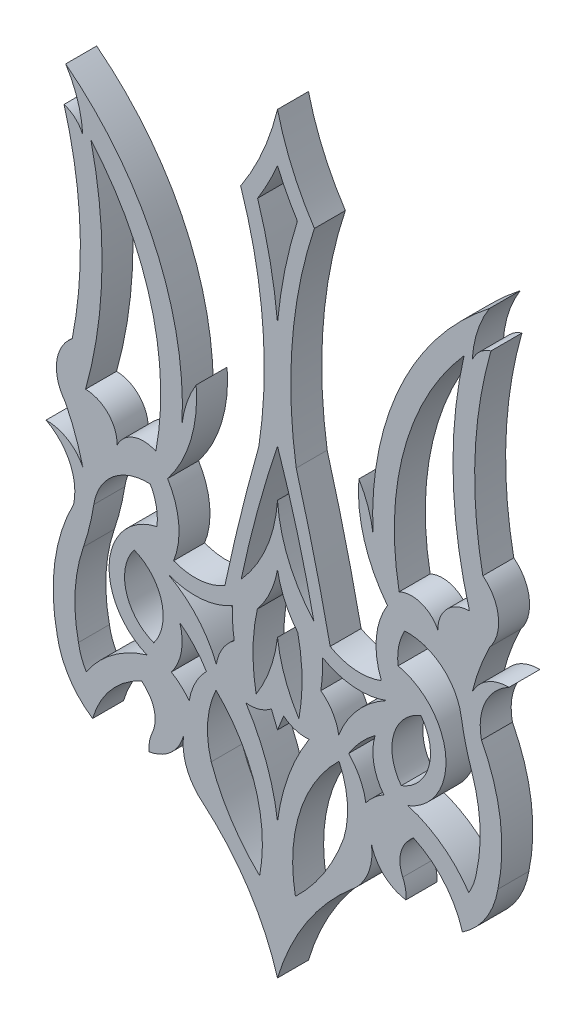
SolidWorks part; units mm, degrees
ref_plane "Спереди" through (0, 0, 0) normal (0, 0, 1) x (1, 0, 0)
ref_plane "Сверху" through (0, 0, 0) normal (0, 1, 0) x (1, 0, 0)
ref_plane "Справа" through (0, 0, 0) normal (1, 0, 0) x (0, 0, -1)
sketch "Эскиз1" [suppressed] plane through (0, 0, 0) normal (0, 0, 1) x (1, 0, 0)
  line L0 (87.6443, -23.7883) -> (87.6443, -6.8916) construction
  line L1 (87.6443, -6.8916) -> (87.6443, 352.3548) construction
  line L3 (87.6443, 68.6318) -> (85.6546, 73.5186)
  line L4 (87.6443, 68.6318) -> (89.6341, 73.5186)
  arc A0 (40.6207, 123.507) -> (44.6469, 97.5316) centre (120.5444, 122.5954) ccw
  arc A1 (40.6207, 123.507) -> (52.5559, 106.1421) centre (-51.0479, 47.7173) cw
  arc A2 (44.6469, 97.5316) -> (48.9353, 94.2011) centre (41.1464, 88.5981) cw
  arc A3 (48.9353, 94.2011) -> (48.9353, 107.9589) centre (131.9116, 101.08) cw
  arc A4 (52.5559, 106.1421) -> (53.1645, 101.095) centre (43.5258, 102.4931) cw
  arc A6 (53.1645, 101.095) -> (49.4634, 108.1691) centre (60.7326, 109.5597) cw
  arc A7 (48.935, 107.9555) -> (49.4634, 108.1691) centre (50.0675, 105.914) cw
  arc A8 (64.6822, 73.5186) -> (59.1188, 62.4923) centre (79.1678, 59.2931) ccw
  arc A9 (59.1188, 62.4923) -> (53.3348, 67.6488) centre (43.2754, 50.5432) ccw
  arc A10 (53.3348, 67.6488) -> (56.4809, 74.2644) centre (31.6379, 82.0231) ccw
  arc A11 (56.4809, 74.2644) -> (56.1084, 82.846) centre (34.8221, 77.623) ccw
  arc A12 (64.6822, 73.5186) -> (56.1084, 82.846) centre (35.8416, 55.6125) ccw
  arc A13 (41.6181, 95.7087) -> (47.5094, 72.7815) centre (35.854, 82.0071) cw
  arc A14 (41.6181, 95.7087) -> (47.5094, 72.7815) centre (53.0477, 86.4251) ccw
  arc A15 (25.6081, 56.3356) -> (38.7862, 66.0056) centre (60.8247, 22.1574) cw
  arc A16 (38.7862, 66.0056) -> (32.0434, 81.1637) centre (52.0503, 80.9846) cw
  arc A17 (40.0148, 95.7087) -> (32.0434, 81.1637) centre (52.4098, 79.4588) ccw
  arc A18 (40.0148, 95.7087) -> (34.589, 93.5264) centre (39.084, 90.1868) ccw
  arc A19 (41.6181, 98.1673) -> (34.1719, 94.2011) centre (40.4092, 91.464) ccw
  arc A20 (30.5806, 109.6374) -> (41.6181, 98.1673) centre (116.5629, 181.3309) ccw
  arc A21 (30.5806, 109.6374) -> (31.6379, 83.1978) centre (-35.2023, 93.7659) cw
  arc A22 (25.6081, 56.3356) -> (31.6379, 83.1978) centre (108.2418, 51.8945) cw
  arc A23 (34.1719, 94.2011) -> (34.589, 93.5264) centre (34.7179, 94.0723) ccw
  arc A24 (72.6436, 90.9214) -> (73.3927, 85.212) centre (115.3568, 93.6216) ccw
  arc A25 (70.0758, 80.9846) -> (73.3927, 85.212) centre (104.2196, 57.6099) cw
  arc A26 (70.0758, 80.9846) -> (60.9509, 89.3983) centre (44.0092, 61.8694) ccw
  arc A27 (60.9509, 89.3983) -> (72.6436, 90.9214) centre (64.518, 107.658) ccw
  arc A28 (80.7379, 32.2385) -> (67.7808, 69.8254) centre (31.257, 36.2081) ccw
  arc A29 (64.9288, 57.4953) -> (67.7808, 69.8254) centre (93.0087, 57.4953) cw
  arc A30 (80.7379, 32.2385) -> (64.9288, 57.4953) centre (119.8675, 74.307) cw
  arc A31 (94.5508, 32.2385) -> (110.3598, 57.4953) centre (55.4212, 74.307) ccw
  arc A32 (110.3598, 57.4953) -> (107.5079, 69.8254) centre (82.28, 57.4953) ccw
  arc A33 (94.5508, 32.2385) -> (107.5079, 69.8254) centre (144.0316, 36.2081) cw
  arc A34 (114.3378, 89.3983) -> (102.6451, 90.9214) centre (110.7707, 107.658) cw
  arc A35 (105.2129, 80.9846) -> (114.3378, 89.3983) centre (131.2795, 61.8694) cw
  arc A36 (105.2129, 80.9846) -> (101.896, 85.212) centre (71.069, 57.6099) ccw
  arc A37 (102.6451, 90.9214) -> (101.896, 85.212) centre (59.9318, 93.6216) cw
  arc A38 (141.1167, 94.2011) -> (140.6996, 93.5264) centre (140.5708, 94.0723) cw
  arc A39 (149.6806, 56.3356) -> (143.6508, 83.1978) centre (67.0469, 51.8945) ccw
  arc A40 (144.708, 109.6374) -> (143.6508, 83.1978) centre (210.491, 93.7659) ccw
  arc A41 (144.708, 109.6374) -> (133.6706, 98.1673) centre (58.7258, 181.3309) cw
  arc A42 (133.6706, 98.1673) -> (141.1167, 94.2011) centre (134.8795, 91.464) cw
  arc A43 (135.2739, 95.7087) -> (140.6996, 93.5264) centre (136.2047, 90.1868) cw
  arc A44 (135.2739, 95.7087) -> (143.2453, 81.1637) centre (122.8789, 79.4588) cw
  arc A45 (136.5025, 66.0056) -> (143.2453, 81.1637) centre (123.2384, 80.9846) ccw
  arc A46 (149.6806, 56.3356) -> (136.5025, 66.0056) centre (114.4639, 22.1574) ccw
  arc A47 (133.6706, 95.7087) -> (127.7793, 72.7815) centre (122.241, 86.4251) cw
  arc A48 (133.6706, 95.7087) -> (127.7793, 72.7815) centre (139.4347, 82.0071) ccw
  arc A49 (110.6065, 73.5186) -> (119.1803, 82.846) centre (139.4471, 55.6125) cw
  arc A50 (118.8077, 74.2644) -> (119.1803, 82.846) centre (140.4665, 77.623) cw
  arc A51 (121.9539, 67.6488) -> (118.8077, 74.2644) centre (143.6508, 82.0231) cw
  arc A52 (116.1699, 62.4923) -> (121.9539, 67.6488) centre (132.0132, 50.5432) cw
  arc A53 (110.6065, 73.5186) -> (116.1699, 62.4923) centre (96.1209, 59.2931) cw
  arc A54 (126.3537, 107.9555) -> (125.8253, 108.1691) centre (125.2211, 105.914) ccw
  arc A55 (122.1242, 101.095) -> (125.8253, 108.1691) centre (114.5561, 109.5597) ccw
  arc A56 (122.7327, 106.1421) -> (122.1242, 101.095) centre (131.7628, 102.4931) ccw
  arc A57 (126.3534, 94.2011) -> (126.3534, 107.9589) centre (43.3771, 101.08) ccw
  arc A58 (130.6418, 97.5316) -> (126.3534, 94.2011) centre (134.1423, 88.5981) ccw
  arc A59 (134.668, 123.507) -> (122.7327, 106.1421) centre (226.3366, 47.7173) ccw
  arc A60 (134.668, 123.507) -> (130.6418, 97.5316) centre (54.7443, 122.5954) cw
  arc A61 (75.9102, 104.8888) -> (87.6443, 132.8603) centre (41.1732, 135.9081) ccw
  arc A62 (75.9102, 104.8888) -> (87.6443, 148.0034) centre (451.7712, 25.7481) cw
  arc A63 (99.3785, 104.8888) -> (87.6443, 132.8603) centre (134.1154, 135.9081) cw
  arc A64 (99.3785, 104.8888) -> (87.6443, 148.0034) centre (-276.4825, 25.7481) ccw
  arc A65 (85.6546, 73.5186) -> (81.8714, 71.5335) centre (82.7705, 74.4176) cw
  arc A66 (87.6443, 53.083) -> (81.8714, 71.5335) centre (17.8027, 41.3588) ccw
  arc A67 (89.6341, 73.5186) -> (93.4173, 71.5335) centre (92.5182, 74.4176) ccw
  arc A68 (87.6443, 53.083) -> (93.4173, 71.5335) centre (157.486, 41.3588) cw
  arc A69 (87.6443, 111.5019) -> (75.9102, 93.6216) centre (57.0652, 118.7792) cw
  arc A70 (75.9102, 93.6216) -> (76.8685, 89.0118) centre (107.3806, 97.7594) ccw
  arc A71 (76.8685, 89.0118) -> (83.3447, 99.1087) centre (-45.6127, 174.6974) ccw
  arc A72 (83.3447, 99.1087) -> (78.1463, 84.8771) centre (62.4821, 98.6641) cw
  arc A73 (80.7379, 75.1856) -> (78.1463, 84.8771) centre (94.8769, 84.1588) cw
  arc A74 (80.7379, 75.1856) -> (83.7649, 75.1856) centre (82.2514, 76.6992) ccw
  arc A75 (83.7649, 75.1856) -> (82.2514, 83.8045) centre (69.0111, 77.037) ccw
  arc A76 (87.6443, 99.1626) -> (82.2514, 83.8045) centre (61.1079, 99.8548) cw
  arc A77 (91.5237, 75.1856) -> (93.0373, 83.8045) centre (106.2776, 77.037) cw
  arc A78 (94.5508, 75.1856) -> (91.5237, 75.1856) centre (93.0373, 76.6992) cw
  arc A79 (94.5508, 75.1856) -> (97.1424, 84.8771) centre (80.4118, 84.1588) ccw
  arc A80 (91.944, 99.1087) -> (97.1424, 84.8771) centre (112.8066, 98.6641) ccw
  arc A81 (98.4202, 89.0118) -> (91.944, 99.1087) centre (220.9014, 174.6974) cw
  arc A82 (99.3785, 93.6216) -> (98.4202, 89.0118) centre (67.908, 97.7594) cw
  arc A83 (87.6443, 111.5019) -> (99.3785, 93.6216) centre (118.2235, 118.7792) ccw
  arc A84 (87.6443, 99.1626) -> (93.0373, 83.8045) centre (114.1808, 99.8548) ccw
  spline S0 degree 3 poles (82.1027, 12.4657) (79.9341, 18.6914) (72.2067, 24.3569) (65.9185, 33.1059) (62.5505, 37.466) (60.1799, 39.943) (59.1555, 43.0897) (57.2647, 45.5543) (57.6286, 48.5225) (57.2368, 50.5201) (57.9183, 52.5735) (56.9495, 53.1909) (55.4861, 53.2614) (56.2486, 51.0634) (55.1896, 49.5498) (54.5036, 47.9051) (53.4075, 46.7279) (51.1035, 46.9894) (53.4402, 48.5489) (52.9045, 50.4248) (53.1315, 52.5819) (50.2686, 54.9996) (47.2077, 56.7477) (43.7411, 62.1873) (40.1307, 57.0478) (36.3563, 55.4003) (34.0123, 52.1175) (31.6232, 49.6208) (29.9193, 47.1505) (28.3136, 45.324) (28.3685, 43.599) (28.0916, 41.1132) (25.4838, 45.8805) (23.6707, 48.1541) (21.3506, 53.1893) (17.5941, 56.1294) (15.6148, 61.936) (15.5097, 68.0525) (15.9741, 74.6221) (17.289, 80.1758) (19.034, 85.376) (20.3139, 90.1381) (21.7721, 94.5747) (21.6409, 98.6721) (22.3333, 102.2806) (22.4635, 106.0403) (21.2552, 109.3896) (20.4336, 112.3281) (19.1765, 114.309) (17.3368, 115.252) (16.6151, 116.5408) (13.9501, 117.1637) (16.6597, 117.6233) (18.0151, 116.3143) (20.2861, 115.5733) (22.0029, 113.6892) (23.906, 112.8857) (24.7011, 110.1686) (25.9462, 111.2271) (24.8035, 113.2315) (24.159, 115.7716) (22.1122, 118.6068) (20.8946, 121.9867) (19.3322, 125.5441) (17.6129, 129.5089) (17.4458, 134.0046) (17.2957, 140.0912) (22.0505, 144.124) (21.6416, 148.9774) (21.7935, 153.6259) (21.4811, 159.1076) (22.6432, 165.8126) (23.1995, 173.1345) (24.6232, 181.9748) (23.765, 191.5281) (23.3918, 198.8905) (20.9362, 204.2846) (19.4503, 205.9635) (18.8575, 209.3893) (19.9586, 207.7428) (21.3919, 207.2624) (22.9247, 206.0347) (23.8774, 204.8209) (24.7322, 203.1653) (25.4143, 204.4362) (24.9731, 205.9617) (24.8711, 208.3515) (23.8043, 211.5847) (22.0026, 215.2682) (20.7759, 217.6358) (18.3336, 220.7887) (20.1657, 220.6691) (22.0637, 219.6809) (26.786, 216.3757) (31.4211, 210.9124) (35.9504, 205.2491) (38.6047, 200.7968) (41.0717, 196.8054) (43.4657, 192.4745) (45.5786, 187.3763) (48.797, 182.0166) (50.8485, 175.8116) (52.3971, 169.5049) (54.0904, 164.0713) (55.1853, 159.4561) (55.6944, 154.6896) (56.8351, 150.296) (56.4354, 145.8923) (56.5698, 142.4952) (56.7674, 140.6512) (56.6429, 138.4535) (58.4364, 140.4087) (58.5125, 143.2164) (59.7639, 147.3027) (59.1349, 150.6113) (60.546, 151.9302) (61.6062, 150.3802) (60.9783, 148.2843) (60.8195, 145.6095) (61.4206, 142.038) (60.3355, 138.7499) (59.3482, 135.2123) (57.8997, 132.2945) (56.5742, 128.4652) (54.2506, 125.5327) (53.3708, 122.086) (51.7176, 121.9147) (50.8205, 120.9474) (52.6711, 119.7166) (53.4663, 117.4305) (55.1877, 114.9802) (55.6358, 111.915) (55.4739, 109.1453) (55.6293, 106.276) (55.2189, 103.833) (54.3757, 101.9514) (54.0729, 100.4765) (53.8467, 98.7589) (56.0297, 98.8443) (57.6189, 98.1528) (59.6896, 98.0729) (61.8788, 98.0468) (64.294, 98.7043) (67.035, 98.9862) (69.132, 99.8917) (71.1395, 100.5472) (71.2883, 102.132) (71.3846, 103.98) (71.6843, 106.4326) (72.3165, 109.0602) (72.9684, 111.8403) (73.7279, 115.3959) (74.8536, 119.4926) (75.763, 123.5727) (76.9652, 127.2471) (78.2259, 131.0447) (79.3431, 135.0503) (80.7614, 142.4724) (83.4282, 150.1397) (82.9512, 158.3066) (84.0107, 163.2854) (83.59, 169.6597) (84.0559, 177.5749) (83.0482, 185.6995) (82.3476, 192.1007) (80.9886, 196.907) (79.5689, 201.5117) (78.8633, 206.1463) (77.0493, 209.8576) (76.689, 212.6324) (75.2575, 214.6117) (76.8358, 216.1245) (77.879, 218.2522) (80.4034, 220.257) (81.8163, 223.0476) (84.1194, 225.3097) (85.0477, 228.2799) (85.6117, 231.0457) (86.1825, 234.1961) (86.3896, 236.5507) (87.6443, 237.7908) knots 0 0 0 0 0.028658 0.043275 0.049534 0.054228 0.058819 0.064724 0.067657 0.072055 0.074743 0.075624 0.077091 0.080033 0.082665 0.085727 0.088171 0.089899 0.093085 0.09504 0.098738 0.10237 0.110881 0.116931 0.12534 0.130966 0.136851 0.143265 0.14693 0.150998 0.153453 0.155706 0.158836 0.169146 0.175056 0.182849 0.190745 0.202253 0.211081 0.2211 0.22852 0.236408 0.243941 0.249861 0.255135 0.260932 0.266943 0.271401 0.275062 0.277427 0.280411 0.282801 0.284651 0.288472 0.292184 0.295167 0.299832 0.302584 0.303471 0.305901 0.311305 0.31655 0.321491 0.327909 0.334558 0.341172 0.348631 0.361775 0.3653 0.370587 0.383408 0.390434 0.401952 0.417351 0.431602 0.445959 0.451733 0.457128 0.459446 0.461227 0.462918 0.467115 0.469213 0.471366 0.472356 0.474352 0.478803 0.483184 0.490226 0.496344 0.499774 0.500928 0.503188 0.510201 0.526825 0.536331 0.543637 0.550744 0.558021 0.566469 0.576206 0.586787 0.596488 0.606229 0.613083 0.618339 0.628411 0.633617 0.638971 0.643137 0.644483 0.645854 0.651354 0.659471 0.66475 0.665493 0.667175 0.670744 0.675956 0.67924 0.687368 0.691401 0.696251 0.702416 0.709709 0.714483 0.715763 0.717201 0.719145 0.723694 0.729034 0.732428 0.737794 0.741861 0.745654 0.749171 0.751124 0.753035 0.755611 0.758771 0.761604 0.764925 0.768896 0.773112 0.777417 0.779908 0.781699 0.784112 0.788713 0.792962 0.796626 0.8019 0.809759 0.816251 0.821199 0.827609 0.834746 0.840382 0.862553 0.871482 0.877812 0.8859 0.90082 0.914379 0.923643 0.930511 0.937411 0.945888 0.95211 0.95598 0.959297 0.961172 0.965011 0.970487 0.975505 0.979301 0.98517 0.98942 0.992411 1 1 1 1
  spline S1 degree 3 poles (82.1027, 12.4657) (84.2993, 11.04) (84.4898, 7.8171) (86.5127, 3.3725) (86.1614, 0.5556) (87.6443, -0.7518) knots 0 0 0 0 0.459955 0.640601 1 1 1 1
  spline S2 degree 3 poles (33.1492, 192.0361) (32.3239, 190.9776) (33.6073, 189.488) (33.8183, 187.2571) (33.5912, 184.1913) (34.768, 180.8287) (34.142, 177.3643) (34.7375, 174.2184) (33.416, 171.4352) (33.916, 167.4649) (33.6419, 163.6672) (32.426, 159.6409) (32.4019, 155.0102) (31.9063, 150.2145) (31.6211, 145.5238) (31.6773, 141.7351) (31.7172, 137.7233) (31.9002, 133.63) (32.978, 129.7883) (33.9667, 126.7415) (34.7739, 124.6373) (35.9477, 123.6027) (36.53, 122.8648) (37.5454, 121.5879) (37.4217, 123.1892) (37.5666, 124.6402) (37.3724, 126.6813) (37.8229, 128.5307) (36.0597, 129.5835) (35.484, 131.9144) (33.8251, 133.8023) (32.9988, 135.8671) (32.5775, 137.8995) (32.7484, 140.1683) (32.6969, 142.6647) (32.7204, 145.3503) (32.6794, 147.1018) (32.7472, 149.4742) (34.0356, 148.8725) (33.4484, 147.6005) (34.7834, 146.6454) (34.9602, 145.1083) (35.8397, 143.8377) (36.3762, 142.2481) (37.3299, 141.4461) (38.2688, 139.6692) (37.6169, 143.0252) (38.8152, 144.4393) (38.7035, 147.2313) (40.2653, 149.5487) (40.4515, 152.7002) (41.8549, 155.6423) (41.9859, 158.862) (43.852, 161.2171) (44.2768, 163.8863) (46.8497, 165.6494) (45.526, 168.176) (45.5393, 170.8684) (44.2898, 173.6945) (43.4083, 176.7928) (42.3605, 179.7494) (41.2587, 183.3179) (39.6884, 186.497) (37.9874, 189.0815) (37.1022, 190.9736) (35.9708, 192.4083) (35.546, 193.416) (34.9644, 194.6072) (34.481, 193.584) (35.0606, 192.9709) (35.4984, 191.9578) (36.1915, 190.5842) (37.1149, 188.6535) (38.6572, 186.6292) (39.1797, 184.1383) (40.3802, 181.9395) (40.9565, 179.5898) (41.4899, 177.0443) (41.4982, 174.3807) (41.5055, 171.851) (41.6679, 169.141) (41.2969, 167.7277) (41.5978, 165.5169) (40.8134, 166.0301) (40.5745, 166.8614) (40.5224, 168.2129) (40.2785, 170.2818) (39.5013, 172.7829) (39.3781, 175.9179) (37.6702, 178.7865) (37.4428, 182.0032) (36.3743, 184.7095) (35.2439, 187.1159) (34.7904, 189.6375) (33.4854, 190.5664) (33.1492, 192.0361) (32.3239, 190.9776) (33.6073, 189.488) knots -0.012612 -0.005761 -0.002075 0 0.007255 0.019718 0.029693 0.047672 0.065407 0.075398 0.089085 0.104151 0.127416 0.139155 0.159578 0.18822 0.203162 0.221786 0.238384 0.256378 0.275818 0.290943 0.298886 0.305592 0.309871 0.315048 0.316266 0.327773 0.336578 0.343481 0.349935 0.360303 0.374097 0.382594 0.389485 0.401439 0.412378 0.423035 0.435398 0.441227 0.444335 0.448491 0.455752 0.462248 0.468297 0.476116 0.48319 0.486816 0.495399 0.506278 0.515895 0.529177 0.542232 0.556628 0.571942 0.583258 0.594987 0.607033 0.616794 0.627412 0.64313 0.656674 0.670279 0.68463 0.706116 0.717022 0.725407 0.734132 0.739585 0.743026 0.745433 0.749878 0.753371 0.760138 0.77021 0.781747 0.793286 0.803307 0.814728 0.82514 0.837744 0.849666 0.859355 0.871506 0.875734 0.877718 0.88086 0.887378 0.895398 0.908474 0.921918 0.936196 0.951395 0.963938 0.974273 0.987388 0.994239 0.997925 1 1.007255 1.019718 1.029693 only from (32.7088, 191.4049) to (32.7088, 191.4049)
  spline S3 degree 3 poles (47.2686, 158.0754) (47.7213, 162.9241) (45.2966, 161.2742) (45.964, 159.5651) (45.3251, 157.6959) (44.4757, 155.1989) (43.5549, 151.8687) (42.7549, 147.538) (42.2447, 143.4146) (41.541, 139.9722) (41.6157, 137.7124) (41.6536, 136.1284) (41.4943, 134.633) (42.3593, 133.2272) (43.8596, 131.8548) (45.2388, 130.3901) (46.1674, 128.8242) (47.1879, 127.4737) (48.047, 126.2665) (49.7786, 126.1221) (49.3203, 127.9742) (49.5218, 129.7723) (49.5314, 132.9689) (49.4172, 136.5451) (49.5613, 140.5116) (49.4214, 144.4013) (48.898, 148.034) (48.8314, 151.5082) (48.2414, 155.3338) (47.2686, 158.0754) (47.7213, 162.9241) (45.2966, 161.2742) knots -0.143996 -0.098331 -0.035995 0 0.019516 0.041316 0.063925 0.095286 0.145724 0.199179 0.268238 0.309127 0.336564 0.356607 0.371756 0.394271 0.417403 0.452475 0.472504 0.488578 0.519641 0.527249 0.545927 0.569891 0.608527 0.666292 0.712585 0.763868 0.81928 0.856004 0.901669 0.964005 1 1.019516 1.041316 1.063925 only from (46.9629, 162.1437) to (46.9629, 162.1437)
  spline S4 degree 3 poles (128.0201, 158.0754) (127.5674, 162.9241) (129.9921, 161.2742) (129.3247, 159.5651) (129.9636, 157.6959) (130.813, 155.1989) (131.7338, 151.8687) (132.5337, 147.538) (133.044, 143.4146) (133.7477, 139.9722) (133.673, 137.7124) (133.6351, 136.1284) (133.7944, 134.633) (132.9293, 133.2272) (131.4291, 131.8548) (130.0499, 130.3901) (129.1213, 128.8242) (128.1008, 127.4737) (127.2417, 126.2665) (125.5101, 126.1221) (125.9684, 127.9742) (125.7669, 129.7723) (125.7573, 132.9689) (125.8715, 136.5451) (125.7274, 140.5116) (125.8672, 144.4013) (126.3907, 148.034) (126.4573, 151.5082) (127.0473, 155.3338) (128.0201, 158.0754) (127.5674, 162.9241) (129.9921, 161.2742) knots -0.143996 -0.098331 -0.035995 0 0.019516 0.041316 0.063925 0.095286 0.145724 0.199179 0.268238 0.309127 0.336564 0.356607 0.371756 0.394271 0.417403 0.452475 0.472504 0.488578 0.519641 0.527249 0.545927 0.569891 0.608527 0.666292 0.712585 0.763868 0.81928 0.856004 0.901669 0.964005 1 1.019516 1.041316 1.063925 only from (128.3258, 162.1437) to (128.3258, 162.1437)
  spline S5 degree 3 poles (142.1395, 192.0361) (142.9648, 190.9776) (141.6814, 189.488) (141.4704, 187.2571) (141.6974, 184.1913) (140.5207, 180.8287) (141.1466, 177.3643) (140.5512, 174.2184) (141.8727, 171.4352) (141.3727, 167.4649) (141.6467, 163.6672) (142.8627, 159.6409) (142.8867, 155.0102) (143.3824, 150.2145) (143.6676, 145.5238) (143.6114, 141.7351) (143.5715, 137.7233) (143.3884, 133.63) (142.3107, 129.7883) (141.322, 126.7415) (140.5148, 124.6373) (139.341, 123.6027) (138.7587, 122.8648) (137.7433, 121.5879) (137.867, 123.1892) (137.7221, 124.6402) (137.9163, 126.6813) (137.4658, 128.5307) (139.229, 129.5835) (139.8047, 131.9144) (141.4636, 133.8023) (142.2899, 135.8671) (142.7112, 137.8995) (142.5403, 140.1683) (142.5918, 142.6647) (142.5683, 145.3503) (142.6093, 147.1018) (142.5414, 149.4742) (141.2531, 148.8725) (141.8402, 147.6005) (140.5053, 146.6454) (140.3285, 145.1083) (139.4489, 143.8377) (138.9125, 142.2481) (137.9587, 141.4461) (137.0198, 139.6692) (137.6717, 143.0252) (136.4735, 144.4393) (136.5852, 147.2313) (135.0234, 149.5487) (134.8372, 152.7002) (133.4338, 155.6423) (133.3028, 158.862) (131.4366, 161.2171) (131.0119, 163.8863) (128.439, 165.6494) (129.7627, 168.176) (129.7494, 170.8684) (130.9989, 173.6945) (131.8804, 176.7928) (132.9282, 179.7494) (134.0299, 183.3179) (135.6003, 186.497) (137.3012, 189.0815) (138.1865, 190.9736) (139.3179, 192.4083) (139.7427, 193.416) (140.3243, 194.6072) (140.8077, 193.584) (140.2281, 192.9709) (139.7902, 191.9578) (139.0971, 190.5842) (138.1737, 188.6535) (136.6315, 186.6292) (136.109, 184.1383) (134.9085, 181.9395) (134.3322, 179.5898) (133.7988, 177.0443) (133.7905, 174.3807) (133.7832, 171.851) (133.6208, 169.141) (133.9918, 167.7277) (133.6909, 165.5169) (134.4753, 166.0301) (134.7142, 166.8614) (134.7663, 168.2129) (135.0101, 170.2818) (135.7874, 172.7829) (135.9106, 175.9179) (137.6185, 178.7865) (137.8459, 182.0032) (138.9144, 184.7095) (140.0448, 187.1159) (140.4983, 189.6375) (141.8033, 190.5664) (142.1395, 192.0361) (142.9648, 190.9776) (141.6814, 189.488) knots -0.012612 -0.005761 -0.002075 0 0.007255 0.019718 0.029693 0.047672 0.065407 0.075398 0.089085 0.104151 0.127416 0.139155 0.159578 0.18822 0.203162 0.221786 0.238384 0.256378 0.275818 0.290943 0.298886 0.305592 0.309871 0.315048 0.316266 0.327773 0.336578 0.343481 0.349935 0.360303 0.374097 0.382594 0.389485 0.401439 0.412378 0.423035 0.435398 0.441227 0.444335 0.448491 0.455752 0.462248 0.468297 0.476116 0.48319 0.486816 0.495399 0.506278 0.515895 0.529177 0.542232 0.556628 0.571942 0.583258 0.594987 0.607033 0.616794 0.627412 0.64313 0.656674 0.670279 0.68463 0.706116 0.717022 0.725407 0.734132 0.739585 0.743026 0.745433 0.749878 0.753371 0.760138 0.77021 0.781747 0.793286 0.803307 0.814728 0.82514 0.837744 0.849666 0.859355 0.871506 0.875734 0.877718 0.88086 0.887378 0.895398 0.908474 0.921918 0.936196 0.951395 0.963938 0.974273 0.987388 0.994239 0.997925 1 1.007255 1.019718 1.029693 only from (142.5799, 191.4049) to (142.5799, 191.4049)
  spline S6 degree 3 poles (93.186, 12.4657) (90.9894, 11.04) (90.7989, 7.8171) (88.776, 3.3725) (89.1273, 0.5556) (87.6443, -0.7518) knots 0 0 0 0 0.459955 0.640601 1 1 1 1
  spline S7 degree 3 poles (93.186, 12.4657) (95.3546, 18.6914) (103.082, 24.3569) (109.3702, 33.1059) (112.7382, 37.466) (115.1088, 39.943) (116.1332, 43.0897) (118.024, 45.5543) (117.6601, 48.5225) (118.0519, 50.5201) (117.3704, 52.5735) (118.3392, 53.1909) (119.8025, 53.2614) (119.0401, 51.0634) (120.0991, 49.5498) (120.7851, 47.9051) (121.8812, 46.7279) (124.1852, 46.9894) (121.8484, 48.5489) (122.3841, 50.4248) (122.1572, 52.5819) (125.02, 54.9996) (128.081, 56.7477) (131.5476, 62.1873) (135.158, 57.0478) (138.9324, 55.4003) (141.2764, 52.1175) (143.6655, 49.6208) (145.3694, 47.1505) (146.9751, 45.324) (146.9202, 43.599) (147.197, 41.1132) (149.8049, 45.8805) (151.618, 48.1541) (153.9381, 53.1893) (157.6945, 56.1294) (159.6739, 61.936) (159.779, 68.0525) (159.3146, 74.6221) (157.9997, 80.1758) (156.2547, 85.376) (154.9747, 90.1381) (153.5166, 94.5747) (153.6478, 98.6721) (152.9553, 102.2806) (152.8252, 106.0403) (154.0334, 109.3896) (154.8551, 112.3281) (156.1122, 114.309) (157.9519, 115.252) (158.6736, 116.5408) (161.3386, 117.1637) (158.629, 117.6233) (157.2736, 116.3143) (155.0026, 115.5733) (153.2858, 113.6892) (151.3827, 112.8857) (150.5876, 110.1686) (149.3425, 111.2271) (150.4852, 113.2315) (151.1297, 115.7716) (153.1765, 118.6068) (154.3941, 121.9867) (155.9564, 125.5441) (157.6757, 129.5089) (157.8429, 134.0046) (157.993, 140.0912) (153.2382, 144.124) (153.6471, 148.9774) (153.4952, 153.6259) (153.8076, 159.1076) (152.6455, 165.8126) (152.0892, 173.1345) (150.6655, 181.9748) (151.5237, 191.5281) (151.8969, 198.8905) (154.3525, 204.2846) (155.8384, 205.9635) (156.4312, 209.3893) (155.33, 207.7428) (153.8968, 207.2624) (152.364, 206.0347) (151.4112, 204.8209) (150.5565, 203.1653) (149.8744, 204.4362) (150.3156, 205.9617) (150.4175, 208.3515) (151.4844, 211.5847) (153.2861, 215.2682) (154.5127, 217.6358) (156.9551, 220.7887) (155.1229, 220.6691) (153.225, 219.6809) (148.5027, 216.3757) (143.8676, 210.9124) (139.3383, 205.2491) (136.684, 200.7968) (134.217, 196.8054) (131.823, 192.4745) (129.7101, 187.3763) (126.4917, 182.0166) (124.4402, 175.8116) (122.8915, 169.5049) (121.1983, 164.0713) (120.1034, 159.4561) (119.5943, 154.6896) (118.4535, 150.296) (118.8533, 145.8923) (118.7188, 142.4952) (118.5213, 140.6512) (118.6458, 138.4535) (116.8523, 140.4087) (116.7762, 143.2164) (115.5248, 147.3027) (116.1538, 150.6113) (114.7427, 151.9302) (113.6825, 150.3802) (114.3104, 148.2843) (114.4692, 145.6095) (113.8681, 142.038) (114.9532, 138.7499) (115.9405, 135.2123) (117.389, 132.2945) (118.7145, 128.4652) (121.0381, 125.5327) (121.9179, 122.086) (123.5711, 121.9147) (124.4682, 120.9474) (122.6176, 119.7166) (121.8223, 117.4305) (120.101, 114.9802) (119.6529, 111.915) (119.8148, 109.1453) (119.6594, 106.276) (120.0698, 103.833) (120.913, 101.9514) (121.2157, 100.4765) (121.442, 98.7589) (119.259, 98.8443) (117.6698, 98.1528) (115.5991, 98.0729) (113.4099, 98.0468) (110.9947, 98.7043) (108.2537, 98.9862) (106.1566, 99.8917) (104.1492, 100.5472) (104.0003, 102.132) (103.9041, 103.98) (103.6044, 106.4326) (102.9722, 109.0602) (102.3203, 111.8403) (101.5608, 115.3959) (100.435, 119.4926) (99.5257, 123.5727) (98.3234, 127.2471) (97.0628, 131.0447) (95.9456, 135.0503) (94.5272, 142.4724) (91.8605, 150.1397) (92.3375, 158.3066) (91.278, 163.2854) (91.6987, 169.6597) (91.2328, 177.5749) (92.2405, 185.6995) (92.9411, 192.1007) (94.3001, 196.907) (95.7197, 201.5117) (96.4254, 206.1463) (98.2393, 209.8576) (98.5997, 212.6324) (100.0312, 214.6117) (98.4528, 216.1245) (97.4097, 218.2522) (94.8853, 220.257) (93.4724, 223.0476) (91.1693, 225.3097) (90.2409, 228.2799) (89.677, 231.0457) (89.1062, 234.1961) (88.8991, 236.5507) (87.6443, 237.7908) knots 0 0 0 0 0.028658 0.043275 0.049534 0.054228 0.058819 0.064724 0.067657 0.072055 0.074743 0.075624 0.077091 0.080033 0.082665 0.085727 0.088171 0.089899 0.093085 0.09504 0.098738 0.10237 0.110881 0.116931 0.12534 0.130966 0.136851 0.143265 0.14693 0.150998 0.153453 0.155706 0.158836 0.169146 0.175056 0.182849 0.190745 0.202253 0.211081 0.2211 0.22852 0.236408 0.243941 0.249861 0.255135 0.260932 0.266943 0.271401 0.275062 0.277427 0.280411 0.282801 0.284651 0.288472 0.292184 0.295167 0.299832 0.302584 0.303471 0.305901 0.311305 0.31655 0.321491 0.327909 0.334558 0.341172 0.348631 0.361775 0.3653 0.370587 0.383408 0.390434 0.401952 0.417351 0.431602 0.445959 0.451733 0.457128 0.459446 0.461227 0.462918 0.467115 0.469213 0.471366 0.472356 0.474352 0.478803 0.483184 0.490226 0.496344 0.499774 0.500928 0.503188 0.510201 0.526825 0.536331 0.543637 0.550744 0.558021 0.566469 0.576206 0.586787 0.596488 0.606229 0.613083 0.618339 0.628411 0.633617 0.638971 0.643137 0.644483 0.645854 0.651354 0.659471 0.66475 0.665493 0.667175 0.670744 0.675956 0.67924 0.687368 0.691401 0.696251 0.702416 0.709709 0.714483 0.715763 0.717201 0.719145 0.723694 0.729034 0.732428 0.737794 0.741861 0.745654 0.749171 0.751124 0.753035 0.755611 0.758771 0.761604 0.764925 0.768896 0.773112 0.777417 0.779908 0.781699 0.784112 0.788713 0.792962 0.796626 0.8019 0.809759 0.816251 0.821199 0.827609 0.834746 0.840382 0.862553 0.871482 0.877812 0.8859 0.90082 0.914379 0.923643 0.930511 0.937411 0.945888 0.95211 0.95598 0.959297 0.961172 0.965011 0.970487 0.975505 0.979301 0.98517 0.98942 0.992411 1 1 1 1
sketch "Эскиз3" plane through (0, 0, 0) normal (0, 0, 1) x (1, 0, 0)
  line L0 (87.6443, -0.7518) -> (87.6443, -30.7439) construction
  line L1 (75.7373, 214.8271) -> (99.5514, 214.8271) construction
  line L2 (87.6443, 214.8271) -> (87.6443, 245.1652) construction
  arc A0 (75.7373, 214.8271) -> (87.6443, 242.1865) centre (3.1746, 262.6778) ccw
  arc A2 (75.7373, 214.8271) -> (81.6055, 144.874) centre (-65.9765, 167.7164) cw
  arc A3 (81.6055, 144.874) -> (70.6377, 100.4834) centre (729.5469, -38.7656) ccw
  arc A4 (70.6377, 100.4834) -> (54.1195, 99.18) centre (61.0278, 116.9518) cw
  arc A5 (54.1195, 99.18) -> (52.147, 121.1645) centre (31.2493, 108.2088) ccw
  arc A6 (52.147, 121.1645) -> (61.3729, 151.9663) centre (17.0866, 148.4485) ccw
  arc A7 (61.3729, 151.9663) -> (56.8067, 138.8308) centre (89.4398, 134.8482) ccw
  arc A8 (56.8067, 138.8308) -> (19.2332, 220.6949) centre (-40.5564, 143.6983) ccw
  arc A9 (19.2332, 220.6949) -> (24.7593, 203.6092) centre (-10.9905, 201.483) cw
  arc A10 (24.7593, 203.6092) -> (18.7084, 209.1008) centre (15.8046, 199.8218) ccw
  arc A11 (18.7084, 209.1008) -> (21.3399, 144.8893) centre (-112.1058, 171.5801) cw
  arc A12 (21.3399, 144.8893) -> (19.102, 126.0824) centre (29.6244, 134.3669) ccw
  arc A13 (19.102, 126.0824) -> (24.7805, 110.6673) centre (-47.0296, 92.9675) cw
  arc A14 (24.7805, 110.6673) -> (12.8982, 117.9136) centre (13.0914, 104.8649) ccw
  arc A15 (12.8982, 117.9136) -> (21.781, 98.7337) centre (4.7748, 102.5045) cw
  arc A16 (21.781, 98.7337) -> (16.4854, 59.6475) centre (73.3534, 71.8446) ccw
  arc A17 (16.4854, 59.6475) -> (27.9301, 41.9549) centre (42.5937, 63.9882) ccw
  arc A18 (27.9301, 41.9549) -> (43.7562, 60.4021) centre (55.9548, 33.9245) cw
  arc A19 (43.7562, 60.4021) -> (46.0707, 57.9309) centre (32.5904, 47.6247) cw
  arc A20 (47.2033, 47.6608) -> (46.2055, 41.7904) centre (57.5332, 42.885) ccw
  arc A21 (46.2055, 41.7904) -> (57.3048, 51.8905) centre (44.028, 55.3321) ccw
  arc A22 (57.3048, 51.8905) -> (63.4952, 36.2204) centre (74.3192, 49.5541) ccw
  arc A23 (63.4952, 36.2204) -> (87.6443, -0.7518) centre (13.2717, -22.957) cw
  arc A24 (111.7935, 36.2204) -> (87.6443, -0.7518) centre (162.017, -22.957) ccw
  arc A25 (117.9838, 51.8905) -> (111.7935, 36.2204) centre (100.9695, 49.5541) cw
  arc A26 (129.0831, 41.7904) -> (117.9838, 51.8905) centre (131.2607, 55.3321) cw
  arc A27 (128.0854, 47.6608) -> (129.0831, 41.7904) centre (117.7555, 42.885) cw
  arc A28 (131.5325, 60.4021) -> (129.218, 57.9309) centre (142.6983, 47.6247) ccw
  arc A29 (147.3585, 41.9549) -> (131.5325, 60.4021) centre (119.3338, 33.9245) ccw
  arc A30 (158.8033, 59.6475) -> (147.3585, 41.9549) centre (132.695, 63.9882) cw
  arc A31 (153.5077, 98.7337) -> (158.8033, 59.6475) centre (101.9353, 71.8446) cw
  arc A32 (162.3905, 117.9136) -> (153.5077, 98.7337) centre (170.5139, 102.5045) ccw
  arc A33 (150.5081, 110.6673) -> (162.3905, 117.9136) centre (162.1973, 104.8649) cw
  arc A34 (156.1867, 126.0824) -> (150.5081, 110.6673) centre (222.3183, 92.9675) ccw
  arc A35 (153.9488, 144.8893) -> (156.1867, 126.0824) centre (145.6643, 134.3669) cw
  arc A36 (156.5803, 209.1008) -> (153.9488, 144.8893) centre (287.3945, 171.5801) ccw
  arc A37 (150.5293, 203.6092) -> (156.5803, 209.1008) centre (159.4841, 199.8218) cw
  arc A38 (156.0554, 220.6949) -> (150.5293, 203.6092) centre (186.2792, 201.483) ccw
  arc A39 (118.482, 138.8308) -> (156.0554, 220.6949) centre (215.8451, 143.6983) cw
  arc A40 (113.9158, 151.9663) -> (118.482, 138.8308) centre (85.8489, 134.8482) cw
  arc A41 (123.1417, 121.1645) -> (113.9158, 151.9663) centre (158.202, 148.4485) cw
  arc A42 (121.1692, 99.18) -> (123.1417, 121.1645) centre (144.0394, 108.2088) cw
  arc A43 (104.651, 100.4834) -> (121.1692, 99.18) centre (114.2609, 116.9518) ccw
  arc A44 (93.6832, 144.874) -> (104.651, 100.4834) centre (-554.2582, -38.7656) cw
  arc A45 (99.5514, 214.8271) -> (93.6832, 144.874) centre (241.2652, 167.7164) ccw
  arc A47 (99.5514, 214.8271) -> (87.6443, 242.1865) centre (172.1141, 262.6778) cw
  arc A48 (46.0707, 57.9309) -> (47.2033, 47.6608) centre (38.1265, 51.8573) cw
  arc A49 (129.218, 57.9309) -> (128.0854, 47.6608) centre (137.1622, 51.8573) ccw
  point P110 (49.2752, 50.7157)
  point P113 (126.0135, 50.7157)
  dimension "D1" = 10
  dimension "D2" = 10
extrude "Бобышка-Вытянуть1" add sketch "Эскиз3" along normal blind 10
sketch "Эскиз4" plane through (0, 0, 0) normal (0, 0, 1) x (1, 0, 0)
  line L0 (87.6443, -0.7518) -> (87.6443, -32.3218) construction
  line L1 (85.6546, 73.5186) -> (87.6443, 68.6318)
  line L2 (87.6443, 68.6318) -> (89.6341, 73.5186)
  arc A0 (87.6443, 148.0034) -> (75.9102, 104.8888) centre (451.7712, 25.7481) ccw
  arc A1 (87.6443, 132.8603) -> (75.9102, 104.8888) centre (41.1732, 135.9081) cw
  arc A2 (67.7808, 69.8254) -> (81.8714, 24.9568) centre (33.1175, 34.2929) cw
  arc A3 (81.8714, 24.9568) -> (66.2431, 49.0031) centre (124.8767, 70.0089) cw
  arc A4 (66.2431, 49.0031) -> (67.7808, 69.8254) centre (94.1751, 57.4083) cw
  arc A5 (87.6443, 42.9742) -> (77.4425, 71.0893) centre (20.2867, 34.4413) ccw
  arc A7 (64.6822, 73.5186) -> (56.1084, 82.846) centre (35.8416, 55.6125) ccw
  arc A8 (64.6822, 73.5186) -> (59.1188, 62.4923) centre (79.1678, 59.2931) ccw
  arc A9 (53.3348, 67.6488) -> (56.1084, 82.846) centre (40.0944, 77.917) ccw
  arc A10 (59.1188, 62.4923) -> (53.3348, 67.6488) centre (43.2754, 50.5432) ccw
  arc A12 (67.908, 77.0685) -> (52.3079, 94.5198) centre (36.5563, 64.7406) ccw
  arc A13 (67.908, 77.0685) -> (73.672, 86.5781) centre (82.0844, 74.9775) cw
  arc A14 (73.672, 86.5781) -> (73.1577, 96.1649) centre (115.3568, 93.6216) cw
  arc A15 (41.3552, 95.8164) -> (47.6907, 73.0153) centre (35.854, 82.0071) cw
  arc A16 (41.3552, 95.8164) -> (47.6907, 73.0153) centre (52.9673, 86.7622) ccw
  arc A17 (87.6443, 113.4827) -> (81.1136, 99.1626) centre (57.0652, 118.7792) cw
  arc A20 (81.1136, 99.1626) -> (80.7379, 75.1856) centre (140.1912, 86.2455) ccw
  arc A21 (80.7379, 75.1856) -> (87.6443, 94.5198) centre (41.6336, 100.055) ccw
  arc A22 (94.5508, 75.1856) -> (87.6443, 94.5198) centre (133.655, 100.055) cw
  arc A23 (94.1751, 99.1626) -> (94.5508, 75.1856) centre (35.0974, 86.2455) cw
  arc A26 (87.6443, 113.4827) -> (94.1751, 99.1626) centre (118.2235, 118.7792) ccw
  arc A27 (133.9335, 95.8164) -> (127.598, 73.0153) centre (122.3214, 86.7622) cw
  arc A28 (133.9335, 95.8164) -> (127.598, 73.0153) centre (139.4347, 82.0071) ccw
  arc A29 (101.6166, 86.5781) -> (102.131, 96.1649) centre (59.9318, 93.6216) ccw
  arc A30 (107.3806, 77.0685) -> (101.6166, 86.5781) centre (93.2043, 74.9775) ccw
  arc A31 (107.3806, 77.0685) -> (122.9808, 94.5198) centre (138.7324, 64.7406) cw
  arc A33 (116.1699, 62.4923) -> (121.9539, 67.6488) centre (132.0132, 50.5432) cw
  arc A34 (121.9539, 67.6488) -> (119.1803, 82.846) centre (135.1943, 77.917) cw
  arc A35 (110.6065, 73.5186) -> (116.1699, 62.4923) centre (96.1209, 59.2931) cw
  arc A36 (110.6065, 73.5186) -> (119.1803, 82.846) centre (139.4471, 55.6125) cw
  arc A38 (87.6443, 42.9742) -> (97.8462, 71.0893) centre (155.002, 34.4413) cw
  arc A39 (109.0456, 49.0031) -> (107.5079, 69.8254) centre (81.1136, 57.4083) ccw
  arc A40 (93.4173, 24.9568) -> (109.0456, 49.0031) centre (50.412, 70.0089) ccw
  arc A41 (107.5079, 69.8254) -> (93.4173, 24.9568) centre (142.1712, 34.2929) ccw
  arc A42 (87.6443, 132.8603) -> (99.3785, 104.8888) centre (134.1154, 135.9081) ccw
  arc A43 (87.6443, 148.0034) -> (99.3785, 104.8888) centre (-276.4825, 25.7481) cw
  arc A44 (77.4425, 71.0893) -> (85.6546, 73.5186) centre (78.6188, 82.2081) ccw
  arc A45 (97.8462, 71.0893) -> (89.6341, 73.5186) centre (96.6699, 82.2081) cw
  arc A46 (46.5701, 116.8463) -> (28.3164, 101.9946) centre (45.7021, 99.2698) ccw
  arc A47 (24.9573, 88.4367) -> (28.3164, 101.9946) centre (-50.7188, 114.3815) ccw
  arc A49 (48.7004, 106.02) -> (45.4623, 68.5209) centre (52.9673, 86.7622) ccw
  arc A50 (37.4121, 98.8909) -> (45.899, 68.3473) centre (52.9673, 86.7622) ccw construction
  arc A52 (151.923, 60.9491) -> (149.4021, 53.997) centre (132.695, 63.9882) cw
  arc A53 (47.6085, 101.7505) -> (46.1975, 117.4761) centre (31.2493, 108.2088) ccw
  arc A54 (48.7004, 106.02) -> (46.5701, 116.8463) centre (31.2493, 108.2088) ccw
  arc A55 (129.8264, 68.5209) -> (149.4021, 53.997) centre (119.3338, 33.9245) cw
  arc A56 (150.3314, 88.4367) -> (146.9723, 101.9946) centre (226.0075, 114.3815) cw
  arc A57 (150.3314, 88.4367) -> (151.923, 60.9491) centre (101.9353, 71.8446) cw
  arc A58 (126.5883, 106.02) -> (129.8264, 68.5209) centre (122.3214, 86.7622) cw
  arc A59 (128.7186, 116.8463) -> (146.9723, 101.9946) centre (129.5865, 99.2698) cw
  arc A60 (126.5883, 106.02) -> (128.7186, 116.8463) centre (144.0394, 108.2088) cw
  arc A75 (28.3709, 96.2178) -> (16.1626, 124.1058) centre (4.7748, 102.5045) ccw
  arc A76 (23.3657, 60.9491) -> (25.8866, 53.997) centre (42.5937, 63.9882) ccw
  arc A77 (28.3709, 96.2178) -> (23.3657, 60.9491) centre (73.3534, 71.8446) ccw
  arc A78 (40.8271, 66.7598) -> (25.8866, 53.997) centre (55.9548, 33.9245) ccw
  arc A80 (23.3657, 60.9491) -> (25.8866, 53.997) centre (42.5937, 63.9882) ccw
  arc A81 (24.9573, 88.4367) -> (23.3657, 60.9491) centre (73.3534, 71.8446) ccw
  arc A82 (45.4623, 68.5209) -> (25.8866, 53.997) centre (55.9548, 33.9245) ccw
  arc A266 (49.8154, 139.1803) -> (14.94, 215.166) centre (-40.5564, 143.6983) ccw
  arc A267 (48.3554, 126.9004) -> (27.3869, 203.4577) centre (-40.5564, 143.6983) ccw
  arc A268 (25.6623, 132.9232) -> (35.854, 122.3882) centre (25.4906, 122.5599) cw
  arc A269 (28.204, 143.5164) -> (25.4371, 211.0307) centre (-112.1058, 171.5801) ccw
  arc A270 (25.6623, 132.9232) -> (27.3869, 203.4577) centre (-112.1058, 171.5801) ccw
  arc A271 (35.854, 122.3882) -> (48.3554, 126.9004) centre (44.3608, 118.3936) cw
  arc A279 (139.4347, 122.3882) -> (126.9333, 126.9004) centre (130.9279, 118.3936) ccw
  arc A280 (149.6264, 132.9232) -> (139.4347, 122.3882) centre (149.798, 122.5599) ccw
  arc A281 (149.6264, 132.9232) -> (147.9018, 203.4577) centre (287.3945, 171.5801) cw
  arc A282 (126.9333, 126.9004) -> (147.9018, 203.4577) centre (215.8451, 143.6983) cw
  arc A322 (94.0669, 214.1199) -> (88.742, 144.1093) centre (241.2652, 167.7164) ccw
  arc A323 (82.7853, 241.0077) -> (94.0669, 214.1199) centre (172.1141, 262.6778) ccw
  arc A324 (94.0669, 214.1199) -> (87.6443, 182.5908) centre (241.2652, 167.7164) ccw
  arc A325 (87.6443, 226.4274) -> (94.0669, 214.1199) centre (172.1141, 262.6778) ccw
  arc A328 (122.9808, 94.5198) -> (102.131, 96.1649) centre (114.2609, 116.9518) cw
  arc A329 (86.5466, 144.1093) -> (81.2218, 214.1199) centre (-65.9765, 167.7164) ccw
  arc A330 (81.2218, 214.1199) -> (92.5034, 241.0077) centre (3.1746, 262.6778) ccw
  arc A331 (87.6443, 182.5908) -> (81.2218, 214.1199) centre (-65.9765, 167.7164) ccw
  arc A332 (81.2218, 214.1199) -> (87.6443, 226.4274) centre (3.1746, 262.6778) ccw
  arc A333 (52.3079, 94.5198) -> (73.1577, 96.1649) centre (61.0278, 116.9518) ccw
  arc A334 (52.3079, 94.5198) -> (73.1577, 96.1649) centre (61.0278, 116.9518) ccw
  point P8 (0, 0)
  point P11 (45.7021, 104.8888)
  point P19 (47.5094, 116.189)
  point P20 (46.291, 116.9518)
  point P33 (47.5094, 119.2749)
  point P40 (0, 0)
  point P41 (0, 0)
  point P42 (45.7195, 116.9518)
  point P56 (50.412, 124.9295)
  point P57 (50.2468, 124.3408)
  point P61 (82.0844, 99.1626)
  point P62 (48.7731, 116.5977)
  point P64 (87.6443, 88.4367)
  point P65 (87.6443, 93.6216)
  point P73 (37.7371, 99.5278)
  point P74 (50.412, 106.3208)
  point P104 (0, 0)
  point P134 (28.7997, 106.8883)
  point P135 (28.3709, 97.1623)
  point P137 (0, 0)
  point P141 (30.7138, 89.7807)
  point P148 (48.3554, 118.3936)
  point P149 (35.854, 94.5198)
  point P153 (48.7731, 116.5977)
  dimension "D7" = 5
  dimension "D8" = 80
  dimension "D9" = 7
  dimension "D1" = 7
  dimension "D2" = 7
  dimension "D3" = 7
  dimension "D4" = 5
  dimension "D5" = 5
  dimension "D6" = 5
extrude "Вырез-Вытянуть4" cut sketch "Эскиз4" along normal blind 10
